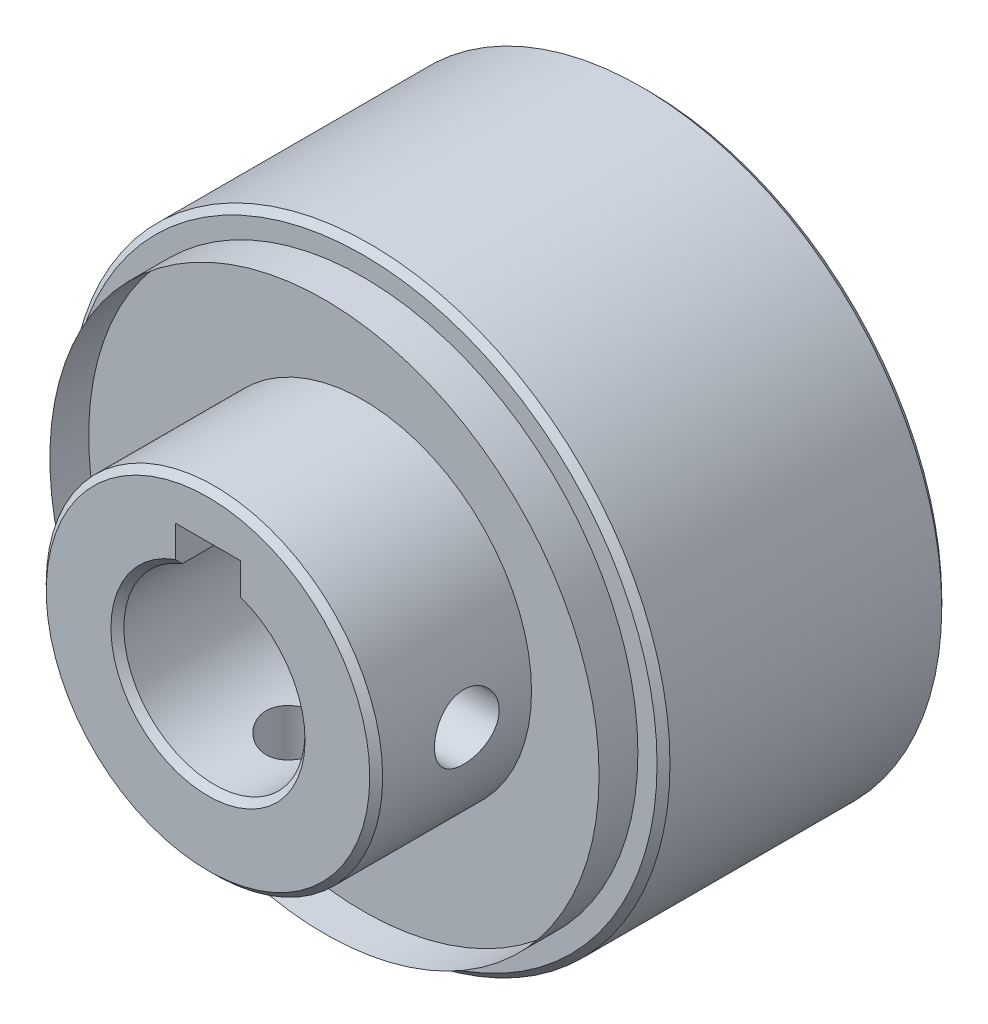
SolidWorks part; units mm, degrees
material "45#"
ref_plane "前视" through (0, 0, 0) normal (0, 0, 1) x (1, 0, 0)
ref_plane "上视" through (0, 0, 0) normal (0, 1, 0) x (1, 0, 0)
ref_plane "右视" through (0, 0, 0) normal (1, 0, 0) x (0, 0, -1)
sketch "草图1" plane through (0, 0, 0) normal (0, 0, 1) x (1, 0, 0)
  circle A0 centre (0, 0) radius 23.2
  circle A1 centre (0, 0) radius 7
  dimension "D1" = 46.4
  dimension "D2" = 14
extrude "凸台-拉伸1" add sketch "草图1" along normal blind 34
sketch "草图2" plane through (0, 0, 34) normal (0, 0, 1) x (1, 0, 0)
  circle A0 centre (0, 0) radius 34.6746
  circle A1 centre (0, 0) radius 13
  dimension "D1" = 26
extrude "切除-拉伸1" cut sketch "草图2" against normal blind 12
hole_wizard "孔1" positions "草图7" profile "草图6" legacy
sketch "草图7" plane through (0, 0, 0) normal (0, 0, -1) x (-1, 0, 0)
  point P0 (0, 0)
sketch "草图6" plane through (0, 0, 0) normal (1, 0, 0) x (0, 1, 0)
  line L0 (0, 0) -> (0, 15)
  line L1 (0, 15) -> (8, 15)
  line L2 (8, 15) -> (8, 0)
  line L3 (8, 0) -> (0, 0)
  line L4 (0, 110) -> (0, -10) construction
  dimension "直径" = 16
  dimension "深度" = 15
sketch "草图3" plane through (0, 0, 34) normal (0, 0, 1) x (1, 0, 0)
  line L0 (0, 0) -> (0, 4.4) construction
  line L2 (-2.5, -0.7) -> (2.5, -0.7)
  line L3 (-2.5, -0.7) -> (-2.5, 9.5)
  line L4 (-2.5, 9.5) -> (2.5, 9.5)
  line L5 (2.5, -0.7) -> (2.5, 9.5)
  line L6 (-2.5, -0.7) -> (2.5, 9.5) construction
  line L7 (-2.5, 9.5) -> (2.5, -0.7) construction
  dimension "D1" = 5
  dimension "D2" = 9.5
extrude "切除-拉伸2" cut sketch "草图3" against normal through all
hole_wizard "M6 螺纹孔1" positions "草图5" profile "草图4" tap size "M6" standard "Iso"
sketch "草图5" plane through (0, 0, 0) normal (0, 1, 0) x (1, 0, 0)
  line L1 (-13, -34) -> (13, -34) construction
  line L2 (0, -34) -> (0, -15) construction
  point P0 (0, -27)
  dimension "D1" = 7
cosmetic thread "孔螺蚊线1" parameters "D2"=6
sketch "草图4" plane through (0, 0, 27) normal (1, 0, 0) x (0, 0, 1)
  line L0 (0, 0) -> (0, 23.2)
  line L1 (0, 23.2) -> (2.5, 23.2)
  line L2 (2.5, 23.2) -> (2.5, 0)
  line L5 (2.5, 0) -> (0, 0)
  line L11 (0, -6.35) -> (0, 107.95) construction
  dimension "通孔螺纹孔钻头直径" = 5
  dimension "通孔螺纹孔钻头深度" = 23.2
hole_wizard "M4 螺纹孔1" positions "草图9" profile "草图8" tap size "M4" standard "Gb"
sketch "草图9" plane through (0, 0, 0) normal (0, 0, -1) x (-1, 0, 0)
  circle A1 centre (0, 0) radius 13 construction
  point P0 (13, 0)
  dimension "D1" = 26
sketch "草图8" plane through (-13, 0, 0) normal (1, 0, 0) x (0, 1, 0)
  line L0 (0, 0) -> (0, 11.0914)
  line L1 (0, 11.0914) -> (1.65, 10.1)
  line L2 (1.65, 10.1) -> (1.65, 0)
  line L5 (1.65, 0) -> (0, 0)
  line L10 (0, 11.0914) -> (-1.65, 10.1) construction
  line L11 (0, -6.35) -> (0, 107.95) construction
  dimension "螺纹孔钻头直径" = 3.3
  dimension "螺纹孔钻头深度" = 10.1
  dimension "导头角度" = 118
cosmetic thread "孔螺蚊线2" parameters "D1"=8, "D2"=4
pattern_circular "阵列(圆周)2" count 6 over 360 about axis through (0, 0, 0) along (0, 0, 1) of "M4 螺纹孔1"
pattern_circular "阵列(圆周)1" count 2 over 90 about axis through (0, 0, 22) along (0, 0, 1) of "M6 螺纹孔1"
sketch "草图10" plane through (0, 0, 22) normal (0, 0, 1) x (1, 0, 0)
  circle A0 centre (0, 0) radius 21.22
  dimension "D1" = 42.44
surface "曲面-拉伸1" sketch "草图10" parameters "D1"=3
chamfer "倒角1" distance 0.5 angle 45 5 edges at (0, -7, 34) (13, 0, 34) (23.2, 0, 22) (23.2, 0, 0) (0, -8, 0)
